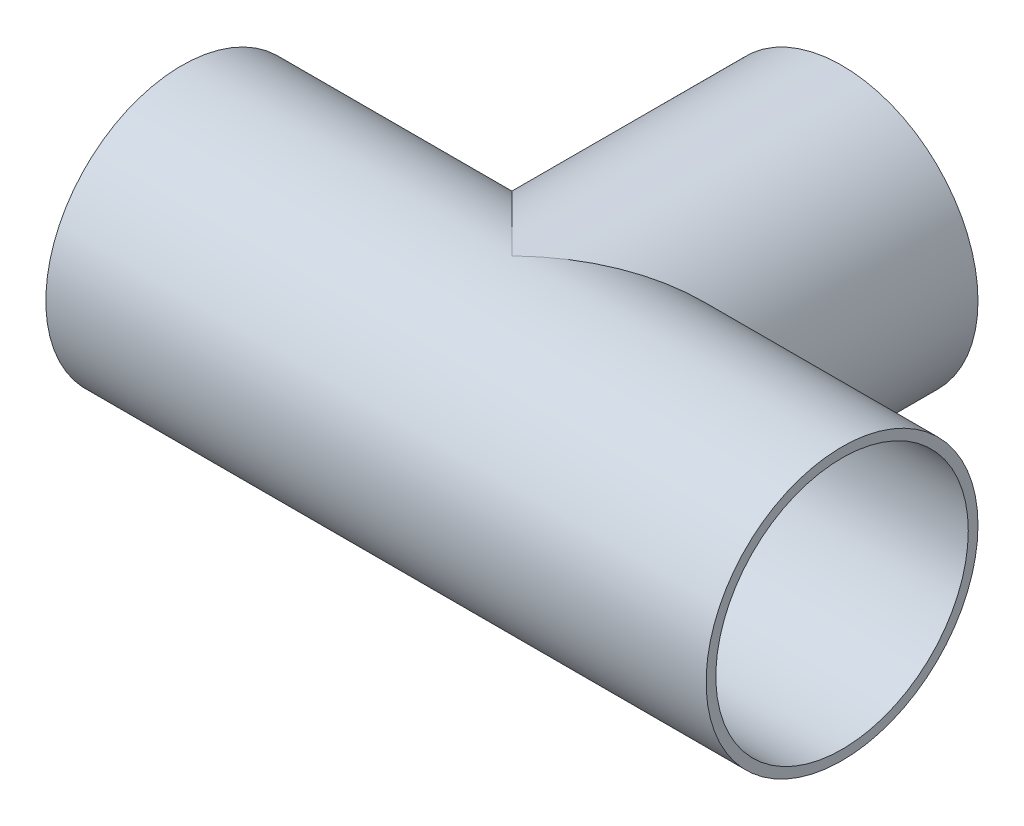
SolidWorks part; units mm, degrees
ref_plane "Front Plane" through (0, 0, 0) normal (0, 0, 1) x (1, 0, 0)
ref_plane "Top Plane" through (0, 0, 0) normal (0, 1, 0) x (1, 0, 0)
ref_plane "Right Plane" through (0, 0, 0) normal (1, 0, 0) x (0, 0, -1)
sketch "Sketch1" plane through (0, 0, 0) normal (1, 0, 0) x (0, 0, -1)
  circle A0 centre (0, 0) radius 35
  dimension "D1" = 70
extrude "Boss-Extrude1" add sketch "Sketch1" against normal blind 170
sketch "Sketch2" plane through (0, 0, 0) normal (1, 0, 0) x (0, 0, -1)
  circle A0 centre (0, 0) radius 32.5
  point P3 (0, 0)
  point P4 (0, 0)
  dimension "D1" = 65
sketch "Sketch4" plane through (0, 0, 0) normal (0, 0, 1) x (1, 0, 0)
  circle A0 centre (-85, 0) radius 35
  dimension "D2" = 70
  dimension "D1" = 85
extrude "Boss-Extrude2" add sketch "Sketch4" against normal blind 85
sketch "Sketch5" plane through (0, 0, -85) normal (0, 0, -1) x (-1, 0, 0)
  circle A0 centre (85, 0) radius 32.5
  dimension "D1" = 65
extrude "Cut-Extrude2" cut sketch "Sketch5" against normal blind 85 contours A0
extrude "Cut-Extrude3" cut sketch "Sketch2" against normal through all contours A0
